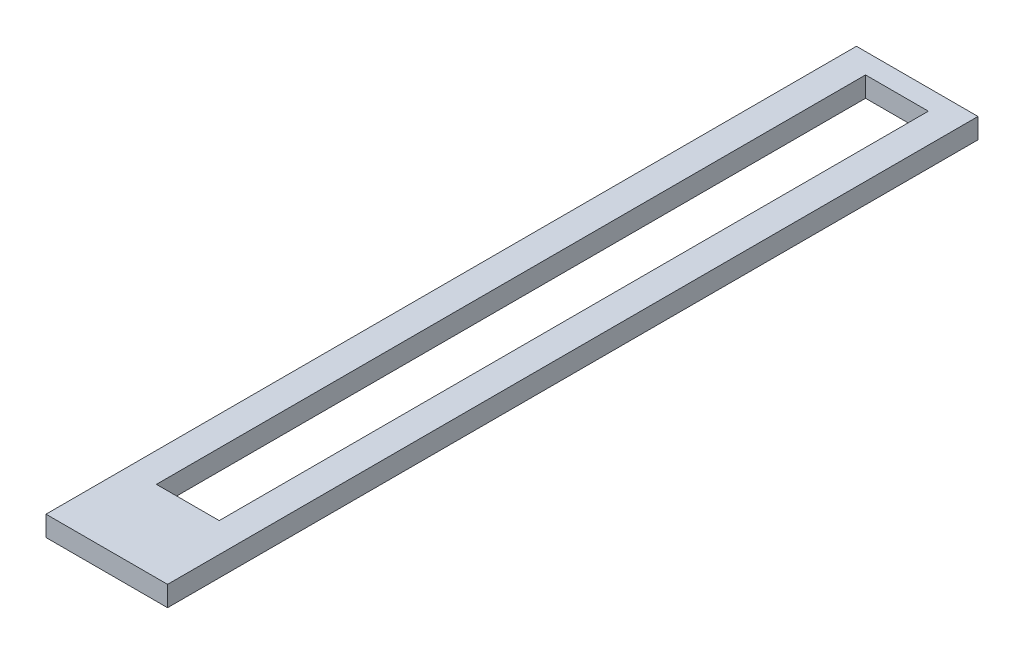
SolidWorks part; units mm, degrees
ref_plane "Plano frontal" through (0, 0, 0) normal (0, 0, 1) x (1, 0, 0)
ref_plane "Plano superior" through (0, 0, 0) normal (0, 1, 0) x (1, 0, 0)
ref_plane "Plano direito" through (0, 0, 0) normal (1, 0, 0) x (0, 0, -1)
sketch "Esboço1" plane through (0, 0, 0) normal (0, 1, 0) x (1, 0, 0)
  line L1 (-15, -100) -> (15, -100)
  line L2 (-15, -100) -> (-15, 100)
  line L3 (-15, 100) -> (15, 100)
  line L4 (15, -100) -> (15, 100)
  line L5 (-15, -100) -> (15, 100) construction
  line L6 (-15, 100) -> (15, -100) construction
  point P0 (0, 0)
  dimension "D1" = 30
  dimension "D2" = 200
extrude "Ressalto-extrusão1" add sketch "Esboço1" along normal blind 5
sketch "Esboço2" plane through (0, 5, 0) normal (0, 1, 0) x (1, 0, 0)
  line L0 (15, 100) -> (-15, 100) construction
  line L1 (-7.75, 95) -> (7.75, 95)
  line L2 (-7.75, 95) -> (-7.75, -80)
  line L3 (-7.75, -80) -> (7.75, -80)
  line L4 (7.75, 95) -> (7.75, -80)
  line L5 (-15, 100) -> (-15, -100) construction
  dimension "D1" = 5
  dimension "D2" = 15.5
  dimension "D3" = 7.25
  dimension "D4" = 175
extrude "Corte-extrusão1" cut sketch "Esboço2" against normal blind 5
